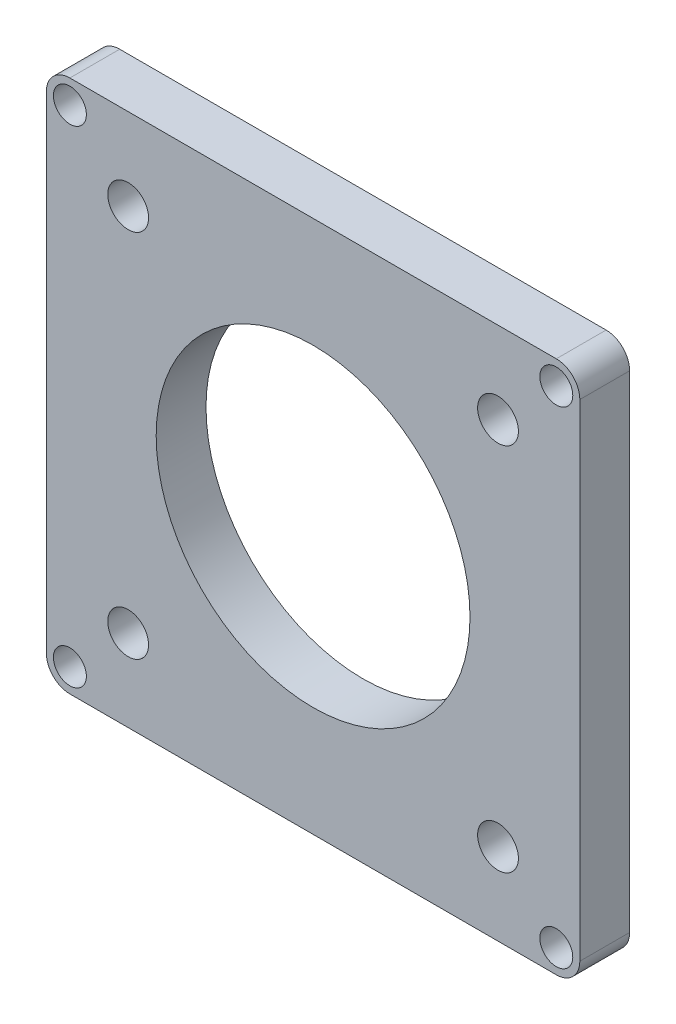
SolidWorks part; units mm, degrees
ref_plane "Front Plane" through (0, 0, 0) normal (0, 0, 1) x (1, 0, 0)
ref_plane "Top Plane" through (0, 0, 0) normal (0, 1, 0) x (1, 0, 0)
ref_plane "Right Plane" through (0, 0, 0) normal (1, 0, 0) x (0, 0, -1)
sketch "Sketch1" plane through (0, 0, 0) normal (0, 0, 1) x (1, 0, 0)
  line L0 (-34, 0) -> (34, 0) construction
  line L1 (-23.57, 23.57) -> (23.57, 23.57) construction
  line L2 (-23.57, 23.57) -> (-23.57, -23.57) construction
  line L3 (-23.57, -23.57) -> (23.57, -23.57) construction
  line L4 (23.57, 23.57) -> (23.57, -23.57) construction
  line L5 (-23.57, 23.57) -> (23.57, -23.57) construction
  line L6 (-23.57, -23.57) -> (23.57, 23.57) construction
  line L7 (-34, 34) -> (34, 34)
  line L8 (-34, 34) -> (-34, -34)
  line L9 (-34, -34) -> (34, -34)
  line L10 (34, 34) -> (34, -34)
  line L11 (-34, 34) -> (34, -34) construction
  line L12 (-34, -34) -> (34, 34) construction
  line L14 (-31, 31) -> (31, 31) construction
  line L15 (-31, 31) -> (-31, -31) construction
  line L16 (-31, -31) -> (31, -31) construction
  line L17 (31, 31) -> (31, -31) construction
  line L18 (-31, 31) -> (31, -31) construction
  line L19 (-31, -31) -> (31, 31) construction
  line L20 (28.575, 28.575) -> (-28.575, 28.575) construction
  line L21 (28.575, 28.575) -> (28.575, -28.575) construction
  line L22 (28.575, -28.575) -> (-28.575, -28.575) construction
  line L23 (-28.575, 28.575) -> (-28.575, -28.575) construction
  line L24 (28.575, 28.575) -> (-28.575, -28.575) construction
  line L25 (28.575, -28.575) -> (-28.575, 28.575) construction
  circle A0 centre (-23.57, 23.57) radius 2.6
  circle A1 centre (23.57, 23.57) radius 2.6
  circle A2 centre (23.57, -23.57) radius 2.6
  circle A3 centre (-23.57, -23.57) radius 2.6
  circle A4 centre (-31, 31) radius 2.1
  circle A5 centre (31, 31) radius 2.1
  circle A6 centre (31, -31) radius 2.1
  circle A7 centre (-31, -31) radius 2.1
  circle A8 centre (0, 0) radius 20
  point P0 (0, 0)
  point P6 (0, 0)
  point P16 (0, 0)
  point P19 (0, 0)
  point P27 (0, 0)
  point P35 (0, 0)
  dimension "D3" = 5.2
  dimension "D7" = 4.2
  dimension "D11" = 40
  dimension "D1" = 47.14
  dimension "D2" = 47.14
  dimension "D5" = 68
  dimension "D8" = 4
  dimension "D9" = 62
  dimension "D10" = 57.15
  dimension "D4" = 4
extrude "Boss-Extrude1" add sketch "Sketch1" along normal mid plane 6.35 contours A7 | L7 L10 L9 L8 | A0 | A4 | A5 | A1 | A2 | A6 | A3 | A8
fillet "Fillet2" radius 3 4 edges at (-34, 34, 0) (-34, -34, 0) (34, -34, 0) (34, 34, 0)
